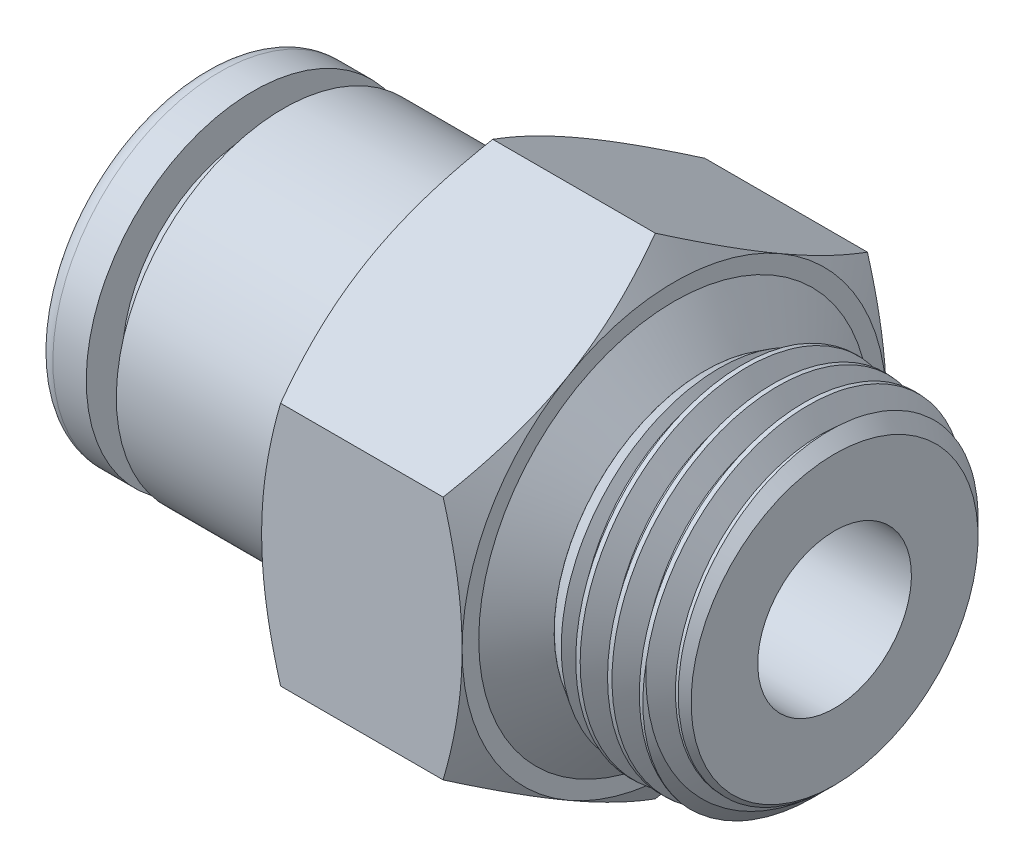
SolidWorks part; units mm, degrees
ref_plane "Front Plane" through (0, 0, 0) normal (0, 0, 1) x (1, 0, 0)
ref_plane "Top Plane" through (0, 0, 0) normal (0, 1, 0) x (1, 0, 0)
ref_plane "Right Plane" through (0, 0, 0) normal (1, 0, 0) x (0, 0, -1)
sketch "Sketch0" plane through (0, 0, 0) normal (0, 0, -1) x (-1, 0, 0)
  line L0 (0, 0) -> (-18.9, 0) construction
  line L1 (0, 5) -> (0, -5) construction
  line L2 (-13.3, 3.175) -> (-13.3, -3.175) construction
  line L3 (-14.1, 5.1435) -> (-14.1, -5.1435) construction
  line L4 (-9.45, 6.35) -> (-9.45, -6.35) construction
  line L5 (-18.9, 2.3) -> (-18.9, -2.3) construction
  point P3 (-13.3, 0)
  point P11 (-9.45, 0)
  point P16 (-14.1, 0)
sketch "Sketch1" plane through (0, 0, 0) normal (0, 0, -1) x (-1, 0, 0)
  line L0 (0, 4.5) -> (0, 3.675)
  line L1 (-0.5, 5) -> (-1.5, 5)
  line L2 (-1.5, 5) -> (-1.5, 3.925)
  line L3 (-1.5, 3.925) -> (-2.4, 3.925)
  line L4 (-2.4, 3.925) -> (-2.4, 5)
  line L5 (-2.4, 5) -> (-14.1, 5)
  line L6 (-14.1, 5.1435) -> (-14.1, -5.1435) construction
  line L7 (0, 0) -> (-18.9, 0) construction
  line L8 (-14.1, 0) -> (-9.45, 0) construction
  line L10 (0, 0) -> (-18.9, 0) construction
  line L11 (-9.45, 3.175) -> (-0.5, 3.175)
  line L12 (0, 5) -> (0, -5) construction
  line L15 (-9.45, 0) -> (-14.1, 0)
  line L16 (-14.1, 0) -> (-14.1, 5)
  line L17 (-9.45, 0) -> (-9.45, 3.175)
  line L18 (-9.45, 6.35) -> (-9.45, -6.35) construction
  arc A0 (0, 4.5) -> (-0.5, 5) centre (-0.5, 4.5) ccw
  arc A1 (-0.5, 3.175) -> (0, 3.675) centre (-0.5, 3.675) ccw
  point P15 (0, 5)
  point P19 (0, 5)
  point P25 (0, 3.175)
  dimension "R" = 0.5
  dimension "D1" = 1.5
  dimension "D3" = 7.85
  dimension "D2" = 0.9
revolve "Revolve2" add sketch "Sketch1" angle 360 about L10
ref_plane "Plane1" through (14.1, 0, 0) normal (1, 0, 0) x (0, 0, -1)
sketch "Sketch2" plane through (14.1, 0, 0) normal (1, 0, 0) x (0, 0, -1)
  circle A0 centre (0, 0) radius 5.1435
  point P5 (0, -5.1435)
extrude "Extrude1" add sketch "Sketch2" along normal up to vertex (4.8 mm away) draft 1.783 separate body up to point (18.9, 0, 0)
sketch "Sketch3" plane through (18.9, 0, 0) normal (1, 0, 0) x (0, 0, -1)
  circle A0 centre (0, 0) radius 4.9941 construction
  circle A1 centre (0, 0) radius 4.9941
curve "Helix/Spiral1" parameters "Height"=5.7236, "Pitch"=0.9236
sketch "Sketch4" plane through (0, 0, 0) normal (0, 0, -1) x (-1, 0, 0)
  line L0 (-19.7659, 5.094) -> (-19.3041, 4.2941) construction
  line L1 (-19.3041, 4.2941) -> (-18.8423, 5.094) construction
  line L2 (-18.8423, 5.094) -> (-19.7659, 5.094) construction
  line L3 (-19.7082, 4.9941) -> (-18.9, 4.9941) construction
  line L4 (-19.3041, 5.094) -> (-19.3041, 4.9941) construction
  line L5 (-19.3041, 4.9941) -> (-19.3041, 4.3941) construction
  line L6 (-19.3041, 4.3941) -> (-19.3041, 4.2941) construction
  line L7 (-19.3618, 4.3941) -> (-19.2464, 4.3941)
  line L8 (-18.8423, 5.094) -> (-19.7082, 4.9941)
  line L9 (-18.8423, 5.094) -> (-19.2464, 4.3941)
  line L10 (-19.7082, 4.9941) -> (-19.3618, 4.3941)
  line L11 (-19.3041, 4.2941) -> (-19.3041, -4.9815) construction
  line L12 (-19.3041, -4.9815) -> (-18.3809, -5.0102) construction
  line L13 (-18.3809, -5.0102) -> (-17.4577, -5.039) construction
  line L14 (-17.4577, -5.039) -> (-16.5345, -5.0677) construction
  line L15 (-16.5345, -5.0677) -> (-15.6113, -5.0964) construction
  line L16 (-18.9, -4.9941) -> (-14.1, -5.1435) construction
  dimension "D1" = 0.9236
  dimension "D2" = 0.1155
sketch "Sketch5" plane through (18.9, 0, 0) normal (1, 0, 0) x (0, 0, -1)
  circle A0 centre (0, 0) radius 4.2941
extrude "Extrude2" cut sketch "Sketch5" against normal up to vertex (4.8 mm away) draft 45 flip side to cut up to point (14.1, 0, 0)
sweep "Cut-Sweep1" cut profiles "Sketch4" path "Helix/Spiral1"
sketch "Sketch5.5" plane through (0, 0, 0) normal (0, 0, 1) x (1, 0, 0)
  line L0 (14.1, -5.1435) -> (15.0232, -5.1148)
  line L1 (19.3041, -4.9815) -> (18.3809, -5.0102) construction
  line L2 (15.0232, -5.1148) -> (15.9464, -5.086)
  line L3 (15.9464, -5.086) -> (15.0232, -4.5148)
  line L4 (15.0232, -4.5148) -> (15.0232, -5.1148) construction
  line L5 (19.3041, 4.9941) -> (19.3041, 4.3941) construction
  line L6 (15.0232, -4.5148) -> (14.1, -4.5436)
  line L7 (14.1, -4.5436) -> (14.1, -5.1435)
  line L8 (14.1, 0) -> (19.3041, 0) construction
  line L9 (14.1, -5.1435) -> (14.1, 5.1435) construction
  line L10 (19.3041, 4.2941) -> (19.3041, -4.9815) construction
revolve "Cut-Revolve1" cut sketch "Sketch5.5" angle 360 about L8
ref_plane "Plane2" through (14.1, 0, 0) normal (1, 0, 0) x (0, 0, -1)
sketch "Sketch6" plane through (14.1, 0, 0) normal (1, 0, 0) x (0, 0, -1)
  circle A0 centre (0, 0) radius 3.175
  circle A2 centre (0, 0) radius 5.1435
  circle A3 centre (0, 0) radius 5.1435
  dimension "D1" = 0
extrude "Extrude3" add sketch "Sketch6" against normal blind 3 draft 45
sketch "Sketch7" plane through (18.9, 0, 0) normal (1, 0, 0) x (0, 0, -1)
  circle A0 centre (0, 0) radius 2.3
extrude "Extrude4" cut sketch "Sketch7" against normal through all
sketch "Sketch8" plane through (14.1, 0, 0) normal (1, 0, 0) x (0, 0, -1)
  line L1 (0, 7.3323) -> (-6.35, 3.6662)
  line L2 (-6.35, 3.6662) -> (-6.35, -3.6662)
  line L3 (-6.35, -3.6662) -> (0, -7.3323)
  line L4 (0, -7.3323) -> (6.35, -3.6662)
  line L5 (6.35, -3.6662) -> (6.35, 3.6662)
  line L6 (6.35, 3.6662) -> (0, 7.3323)
  circle A0 centre (0, 0) radius 6.35 construction
  circle A3 centre (0, 0) radius 5
extrude "Extrude5" add sketch "Sketch8" against normal blind 6
sketch "Sketch9" plane through (14.1, 0, 0) normal (1, 0, 0) x (0, 0, -1)
  circle A0 centre (0, 0) radius 6.35 construction
  circle A1 centre (0, 0) radius 6.35
extrude "Extrude6" cut sketch "Sketch9" against normal up to vertex draft 60 flip side to cut
sketch "Sketch10" plane through (8.1, 0, 0) normal (-1, 0, 0) x (0, 0, 1)
  circle A1 centre (0, 0) radius 6.35
  circle A2 centre (0, 0) radius 6.35
  dimension "D1" = 0
extrude "Extrude7" cut sketch "Sketch10" against normal up to vertex draft 60 flip side to cut
sketch "Sketch12" plane through (0, 0, 0) normal (0, 0, 1) x (1, 0, 0)
  line L0 (0, 0) -> (18.9, 0) construction
  line L1 (0, 4.5) -> (0, -4.5) construction
  line L3 (15.0232, -4.5148) -> (14.1, -4.5436) construction
  line L8 (14.1, -5.1435) -> (14.1, -5.8516)
  line L9 (14.5234, -4.5304) -> (14.1, -5.1435)
  line L10 (14.5234, -4.5304) -> (15.0232, -4.5148)
  line L11 (14.1, -5.8516) -> (15.0232, -4.5148)
  dimension "D1" = 0.5
revolve "Revolve3" add sketch "Sketch12" angle 360 about L0
equation "\"Height@Helix/Spiral1\" = \"Pitch@Helix/Spiral1\" + \"Thread Length@Sketch0\""
equation "\"D1@Sketch4\" = \"Pitch@Helix/Spiral1\""
equation "\"D2@Sketch4\" = \"D1@Sketch4\" * 1 / 8"
